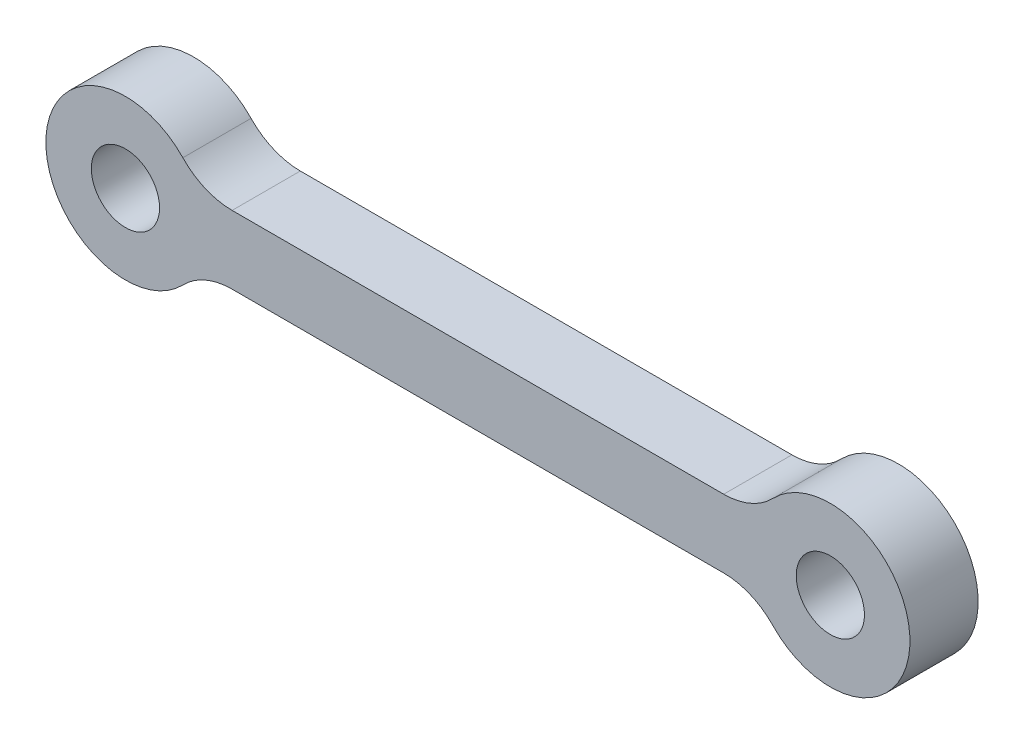
SolidWorks part; units mm, degrees
ref_plane "Front Plane" through (0, 0, 0) normal (0, 0, 1) x (1, 0, 0)
ref_plane "Top Plane" through (0, 0, 0) normal (0, 1, 0) x (1, 0, 0)
ref_plane "Right Plane" through (0, 0, 0) normal (1, 0, 0) x (0, 0, -1)
sketch "Sketch1" plane through (0, 0, 0) normal (0, 0, 1) x (1, 0, 0)
  line L0 (4.6904, 1.5) -> (26.3096, 1.5)
  line L1 (4.6904, -1.5) -> (26.3096, -1.5)
  arc A0 (2.5256, 2.4231) -> (2.5256, -2.4231) centre (0, 0) ccw
  arc A1 (28.4744, -2.4231) -> (28.4744, 2.4231) centre (31, 0) ccw
  arc A2 (26.3096, -1.5) -> (28.4744, -2.4231) centre (26.3096, -4.5) cw
  arc A3 (26.3096, 1.5) -> (28.4744, 2.4231) centre (26.3096, 4.5) ccw
  arc A4 (4.6904, -1.5) -> (2.5256, -2.4231) centre (4.6904, -4.5) ccw
  arc A5 (4.6904, 1.5) -> (2.5256, 2.4231) centre (4.6904, 4.5) cw
  circle A6 centre (0, 0) radius 1.5
  circle A7 centre (31, 0) radius 1.5
  point P1 (-3.5, 0)
  point P4 (34.5, 0)
  dimension "D1" = 7
  dimension "D3" = 3
  dimension "D5" = 3
  dimension "D6" = 31
  dimension "D2" = 38
  dimension "D4" = 3
extrude "Boss-Extrude1" add sketch "Sketch1" along normal blind 3
